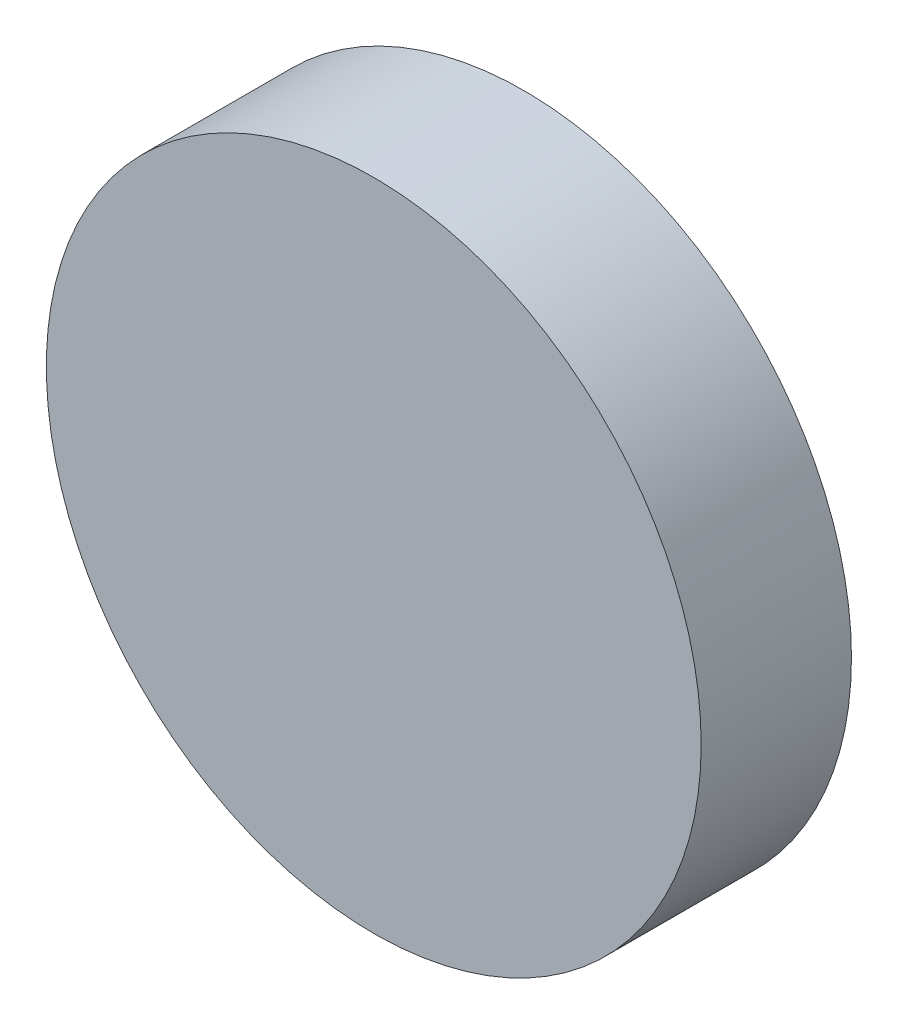
SolidWorks part; units mm, degrees
material "未指定"
ref_plane "正面" through (0, 0, 0) normal (0, 0, 1) x (1, 0, 0)
ref_plane "平面" through (0, 0, 0) normal (0, 1, 0) x (1, 0, 0)
ref_plane "右側面" through (0, 0, 0) normal (1, 0, 0) x (0, 0, -1)
sketch "ｽｹｯﾁ1" plane through (0, 0, 0) normal (0, 0, 1) x (1, 0, 0)
  circle A0 centre (0, 0) radius 15.25
  dimension "D1" = 30.5
extrude "ﾎﾞｽ - 押し出し1" add sketch "ｽｹｯﾁ1" along normal blind 7
